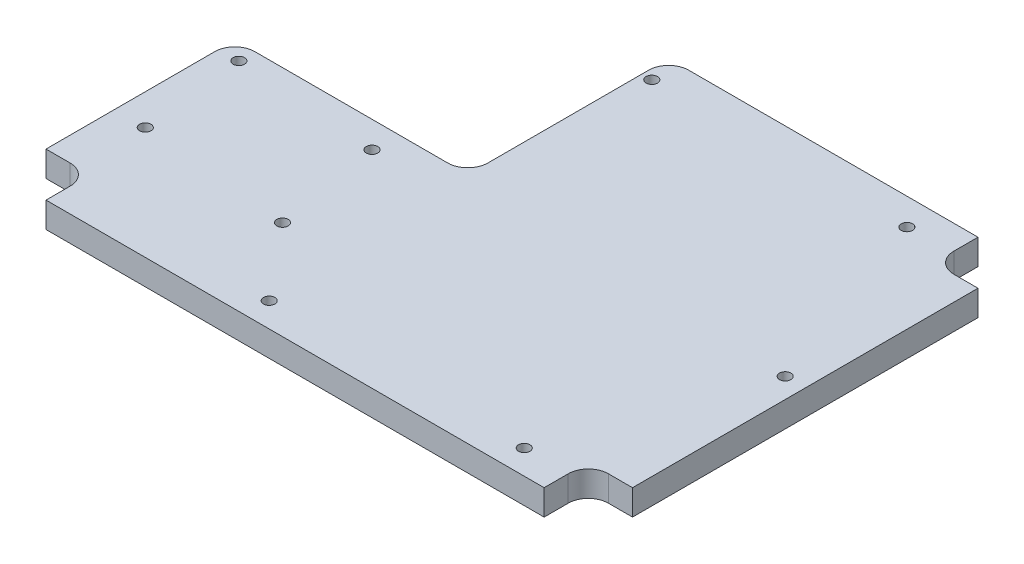
SolidWorks part; units mm, degrees
ref_plane "Front Plane" through (0, 0, 0) normal (0, 0, 1) x (1, 0, 0)
ref_plane "Top Plane" through (0, 0, 0) normal (0, 1, 0) x (1, 0, 0)
ref_plane "Right Plane" through (0, 0, 0) normal (1, 0, 0) x (0, 0, -1)
sketch "Sketch1" plane through (0, 0, 0) normal (0, 1, 0) x (1, 0, 0)
  line L0 (-73, -1) -> (-73, -43)
  line L1 (-73, -43) -> (-67, -43)
  line L2 (-62, -48) -> (-62, -54)
  line L3 (-62, -54) -> (62, -54)
  line L4 (62, -54) -> (62, -48)
  line L5 (67, -43) -> (73, -43)
  line L6 (73, -43) -> (73, 43)
  line L7 (73, 43) -> (67, 43)
  line L8 (62, 48) -> (62, 54)
  line L9 (62, 54) -> (-10, 54)
  line L10 (-15, 49) -> (-15, 9)
  line L11 (-20, 4) -> (-68, 4)
  line L12 (73, 0) -> (0, 0) construction
  line L13 (0, 0) -> (-72.899, 0) construction
  line L14 (-73, 4) -> (-73, -1) construction
  line L15 (-73, -1) -> (-73.0008, -1.0015) construction
  line L16 (-68, 4) -> (-73, 4) construction
  line L17 (0, -54) -> (0, 0) construction
  line L18 (54.15, -51.1) -> (-15.7014, -51.1) construction
  line L19 (54.15, -51.1) -> (60.5, -51.1) construction
  line L21 (-70.4934, 2.575) -> (-20.2014, 2.575) construction
  line L22 (-70.4934, 2.575) -> (-70.4934, -34.636) construction
  line L23 (-70.4934, -34.636) -> (-20.2014, -34.636) construction
  line L24 (-20.2014, 2.575) -> (-20.2014, -34.636) construction
  line L29 (-12.5264, 47.325) -> (50.975, 47.325) construction
  line L30 (-12.5264, -47.9249) -> (-12.5264, 47.325) construction
  line L31 (50.975, -47.9249) -> (-12.5264, -47.9249) construction
  line L32 (50.975, 47.325) -> (50.975, -47.9249) construction
  line L33 (-15.7014, 50.5) -> (-15.7014, -51.1) construction
  line L35 (60.5, 50.5) -> (60.5, -51.1) construction
  line L36 (60.5, 50.5) -> (-15.7014, 50.5) construction
  line L37 (54.15, 50.5) -> (54.15, -51.1) construction
  arc A0 (-73, -1) -> (-68, 4) centre (-68, -1) cw
  arc A1 (-62, -48) -> (-67, -43) centre (-67, -48) ccw
  arc A2 (62, -48) -> (67, -43) centre (67, -48) cw
  arc A3 (62, 48) -> (67, 43) centre (67, 48) ccw
  arc A4 (-15, 49) -> (-10, 54) centre (-10, 49) cw
  arc A5 (-20, 4) -> (-15, 9) centre (-20, 9) ccw
  circle A6 centre (68, 0) radius 1.4224
  circle A7 centre (-68, 0) radius 1.4224
  circle A11 centre (-27.6944, -29.429) radius 1.4224
  circle A12 centre (-65.2864, -26) radius 1.4224
  circle A13 centre (-32.2664, -2.5812) radius 1.4224
  circle A15 centre (-12.5264, -47.9249) radius 1.4224
  circle A16 centre (50.975, -47.9249) radius 1.4224
  circle A17 centre (-12.5264, 47.325) radius 1.4224
  circle A18 centre (50.975, 47.325) radius 1.4224
  point P8 (0, -54)
  point P13 (73, 0)
  point P19 (-62, -43)
  dimension "D6" = 5
  dimension "D7" = 5
  dimension "D8" = 5
  dimension "D9" = 5
  dimension "D10" = 5
  dimension "D11" = 5
  dimension "D13" = 2.8448
  dimension "D25" = 101.6
  dimension "D1" = 146
  dimension "D2" = 11
  dimension "D3" = 108
  dimension "D4" = 88
  dimension "D5" = 50
  dimension "D12" = 5
  dimension "D14" = 5
  dimension "D15" = 3.1751
  dimension "D16" = 12.5
  dimension "D17" = 3.5
  dimension "D18" = 3.175
  dimension "D19" = 3.175
  dimension "D21" = 3.175
  dimension "D22" = 6.35
  dimension "D24" = 76.2014
  dimension "D26" = 50.292
  dimension "D27" = 37.211
  dimension "D28" = 32.004
  dimension "D29" = 7.493
  dimension "D30" = 45.085
  dimension "D31" = 28.575
  dimension "D32" = 5.1562
  dimension "D33" = 12.065
  dimension "D35" = 17
  dimension "D36" = 4.5
extrude "Boss-Extrude1" add sketch "Sketch1" along normal blind 6.35
